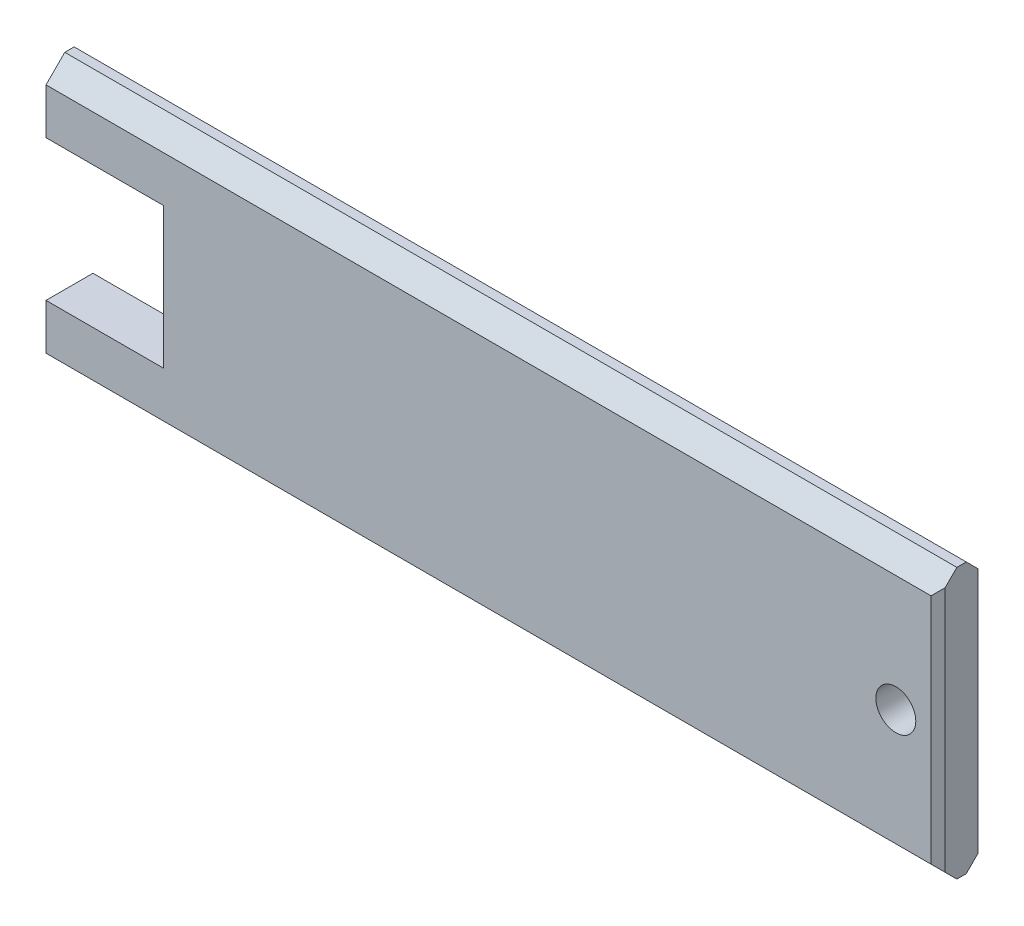
SolidWorks part; units mm, degrees
material "Q355"
ref_plane "前视基准面" through (0, 0, 0) normal (0, 0, 1) x (1, 0, 0)
ref_plane "上视基准面" through (0, 0, 0) normal (0, 1, 0) x (1, 0, 0)
ref_plane "右视基准面" through (0, 0, 0) normal (1, 0, 0) x (0, 0, -1)
sketch "草图1" plane through (0, 0, 0) normal (0, 0, 1) x (1, 0, 0)
  line L1 (-190, 57.5) -> (190, 57.5)
  line L2 (-190, 57.5) -> (-190, -57.5)
  line L3 (-190, -57.5) -> (190, -57.5)
  line L4 (190, 57.5) -> (190, -57.5)
  line L5 (-190, 57.5) -> (190, -57.5) construction
  line L6 (-190, -57.5) -> (190, 57.5) construction
  point P0 (0, 0)
  dimension "D1" = 115
  dimension "D2" = 380
extrude "凸台-拉伸1" add sketch "草图1" along normal blind 20
sketch "草图2" plane through (0, 0, 20) normal (0, 0, 1) x (1, 0, 0)
  line L0 (-190, 0) -> (137.3626, 0) construction
  line L1 (-190, 57.5) -> (-190, -57.5) construction
  line L3 (190, -57.5) -> (190, 57.5) construction
  circle A0 centre (-13, 0) radius 10 construction
  circle A1 centre (172, 0) radius 8.5
  dimension "D1" = 20
  dimension "D3" = 17
  dimension "D2" = 18
  dimension "D4" = 185
extrude "切除-拉伸1" cut sketch "草图2" against normal blind 20
chamfer "倒角1" distance 3 angle 45 2 edges at (190, 0, 0) (190, 0, 20)
sketch "草图3" plane through (0, 0, 20) normal (0, 0, 1) x (1, 0, 0)
  line L0 (-190, 57.5) -> (-190, -57.5) construction
  line L1 (-190, 30) -> (-140, 30)
  line L2 (-190, 30) -> (-190, -30)
  line L3 (-190, -30) -> (-140, -30)
  line L4 (-140, 30) -> (-140, -30)
  line L5 (-190, 0) -> (190, 0) construction
  line L6 (190, 57.5) -> (190, -57.5) construction
  dimension "D1" = 60
  dimension "D2" = 50
extrude "切除-拉伸2" cut sketch "草图3" against normal through all
chamfer "倒角2" distance 8 angle 45 4 edges at (-1.5, 57.5, 20) (-1.5, 57.5, 0) (-1.5, -57.5, 0) (-1.5, -57.5, 20)
